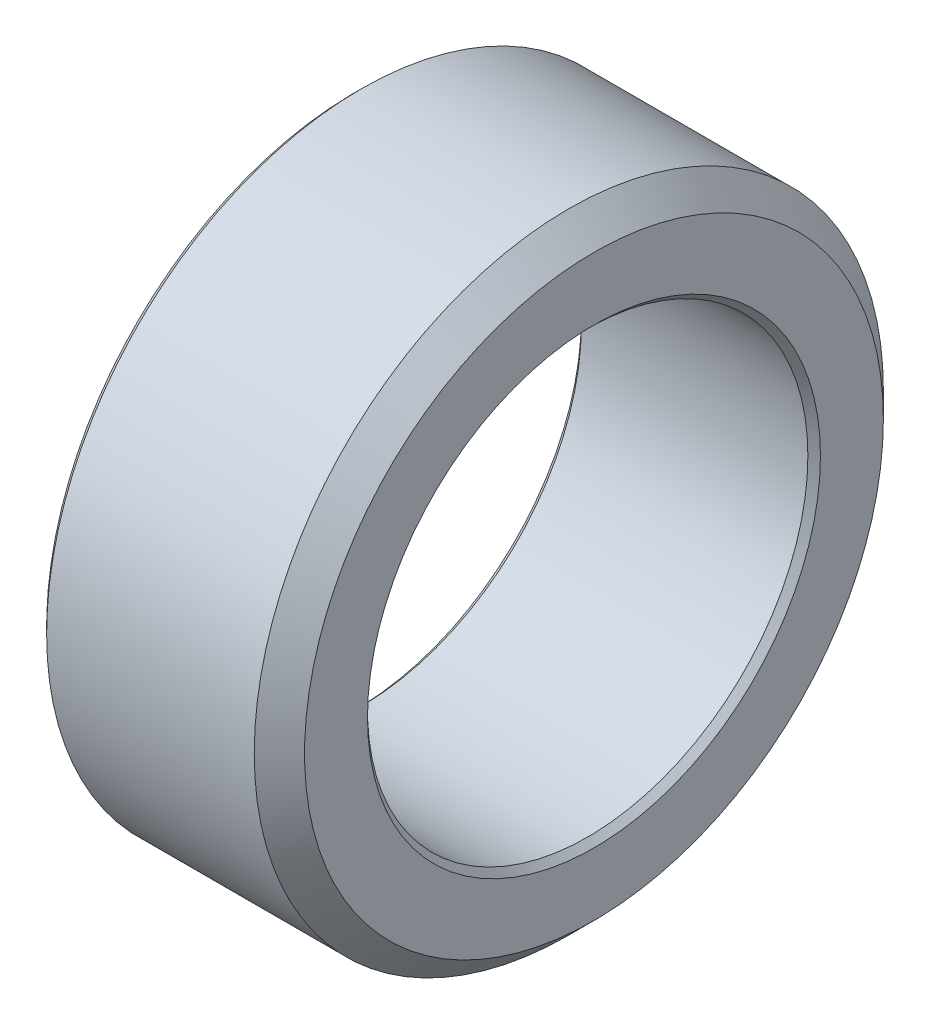
SolidWorks part; units mm, degrees
material "20"
ref_plane "前视基准面" through (0, 0, 0) normal (0, 0, 1) x (1, 0, 0)
ref_plane "上视基准面" through (0, 0, 0) normal (0, 1, 0) x (1, 0, 0)
ref_plane "右视基准面" through (0, 0, 0) normal (1, 0, 0) x (0, 0, -1)
sketch "草图1" plane through (0, 0, 0) normal (1, 0, 0) x (0, 0, -1)
  circle A0 centre (0, 0) radius 50
  circle A1 centre (0, 0) radius 35
  dimension "D1" = 100
  dimension "D2" = 70
extrude "凸台-拉伸1" add sketch "草图1" along normal blind 38
chamfer "倒角1" distance 1 angle 45 3 edges at (0, 0, -35) (0, 0, -50) (38, 0, -35)
chamfer "倒角2" distance 4 angle 45 1 edges at (38, 0, -50)
